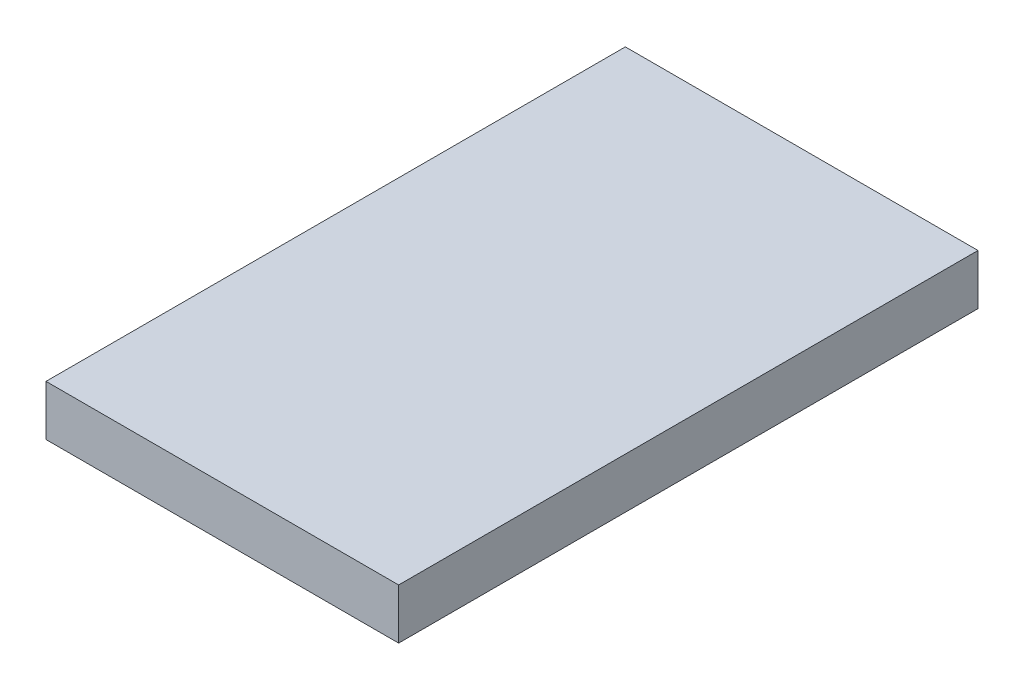
SolidWorks part; units mm, degrees
ref_plane "Front Plane" through (0, 0, 0) normal (0, 0, 1) x (1, 0, 0)
ref_plane "Top Plane" through (0, 0, 0) normal (0, 1, 0) x (1, 0, 0)
ref_plane "Right Plane" through (0, 0, 0) normal (1, 0, 0) x (0, 0, -1)
sketch "Sketch1" plane through (0, 0, 0) normal (0, 1, 0) x (1, 0, 0)
  line L1 (0, 0) -> (14, 0)
  line L2 (0, 0) -> (0, 23)
  line L3 (0, 23) -> (14, 23)
  line L4 (14, 0) -> (14, 23)
  dimension "D1" = 14
  dimension "D2" = 23
extrude "Boss-Extrude1" add sketch "Sketch1" along normal blind 2
